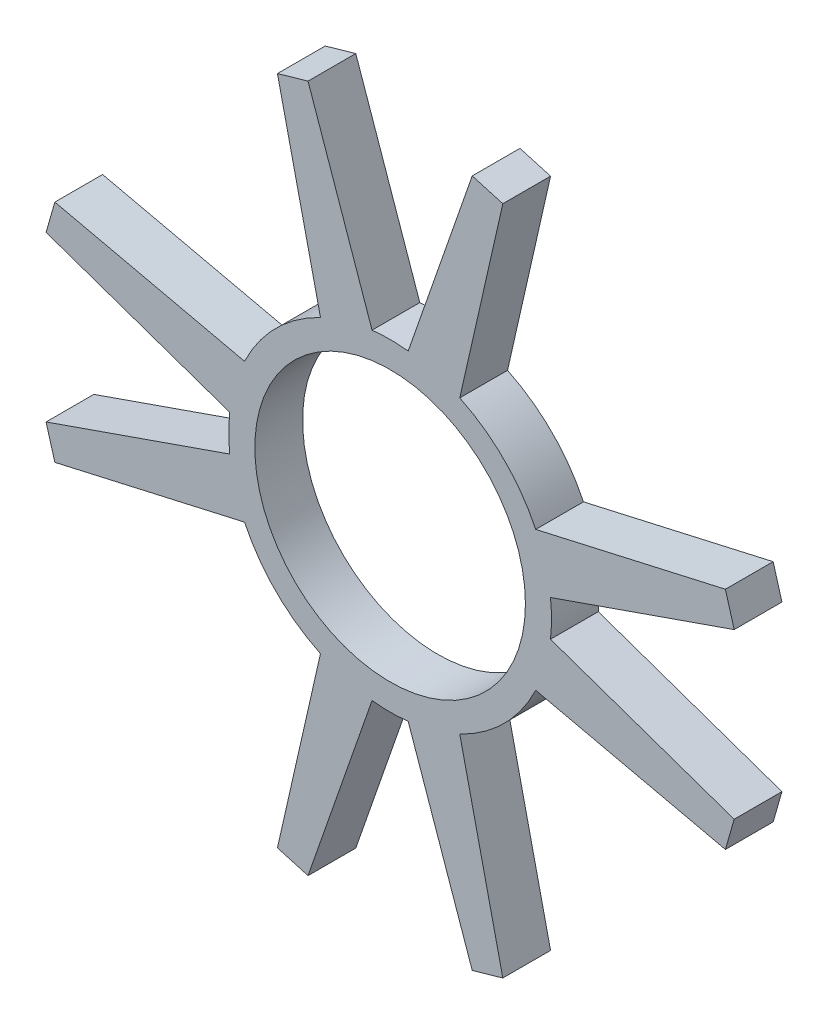
SolidWorks part; units mm, degrees
ref_plane "Front Plane" through (0, 0, 0) normal (0, 0, 1) x (1, 0, 0)
ref_plane "Top Plane" through (0, 0, 0) normal (0, 1, 0) x (1, 0, 0)
ref_plane "Right Plane" through (0, 0, 0) normal (1, 0, 0) x (0, 0, -1)
sketch "草图1" plane through (0, 0, 0) normal (0, 0, 1) x (1, 0, 0)
  line L0 (21.0642, 7.0804) -> (9.1461, 4.376)
  line L1 (21.6155, 5.1578) -> (10.0753, 1.1356)
  line L2 (5.1578, 21.6155) -> (1.1356, 10.0753)
  line L3 (-7.0804, 21.0642) -> (-4.376, 9.1461)
  line L4 (-5.1578, 21.6155) -> (-1.1356, 10.0753)
  line L5 (-7.0804, 21.0642) -> (-5.1578, 21.6155)
  line L8 (7.0804, 21.0642) -> (4.376, 9.1461)
  line L9 (7.0804, 21.0642) -> (5.1578, 21.6155)
  line L10 (21.6155, -5.1578) -> (10.0753, -1.1356)
  line L11 (21.0642, -7.0804) -> (21.6155, -5.1578)
  line L12 (21.0642, -7.0804) -> (9.1461, -4.376)
  line L13 (21.0642, 7.0804) -> (21.6155, 5.1578)
  line L14 (7.0804, -21.0642) -> (4.376, -9.1461)
  line L15 (5.1578, -21.6155) -> (1.1356, -10.0753)
  line L16 (-5.1578, -21.6155) -> (-1.1356, -10.0753)
  line L17 (-7.0804, -21.0642) -> (-5.1578, -21.6155)
  line L18 (-7.0804, -21.0642) -> (-4.376, -9.1461)
  line L19 (7.0804, -21.0642) -> (5.1578, -21.6155)
  line L20 (-21.0642, -7.0804) -> (-9.1461, -4.376)
  line L21 (-21.6155, -5.1578) -> (-10.0753, -1.1356)
  line L22 (-21.6155, 5.1578) -> (-10.0753, 1.1356)
  line L23 (-21.0642, 7.0804) -> (-21.6155, 5.1578)
  line L24 (-21.0642, 7.0804) -> (-9.1461, 4.376)
  line L25 (-21.0642, -7.0804) -> (-21.6155, -5.1578)
  arc A0 (-4.376, 9.1461) -> (-9.1461, 4.376) centre (0, 0) ccw
  circle A1 centre (0, 0) radius 8.5
  arc A3 (1.1356, 10.0753) -> (-1.1356, 10.0753) centre (0, 0) ccw
  arc A4 (-10.0753, 1.1356) -> (-10.0753, -1.1356) centre (0, 0) ccw
  arc A5 (-9.1461, -4.376) -> (-4.376, -9.1461) centre (0, 0) ccw
  arc A6 (-1.1356, -10.0753) -> (1.1356, -10.0753) centre (0, 0) ccw
  arc A7 (4.376, -9.1461) -> (9.1461, -4.376) centre (0, 0) ccw
  arc A8 (10.0753, -1.1356) -> (10.0753, 1.1356) centre (0, 0) ccw
  arc A9 (9.1461, 4.376) -> (4.376, 9.1461) centre (0, 0) ccw
  point P50 (0, 0)
  point P51 (0, 0)
  dimension "D1" = 4
extrude "凸台-拉伸1" add sketch "草图1" along normal blind 3
